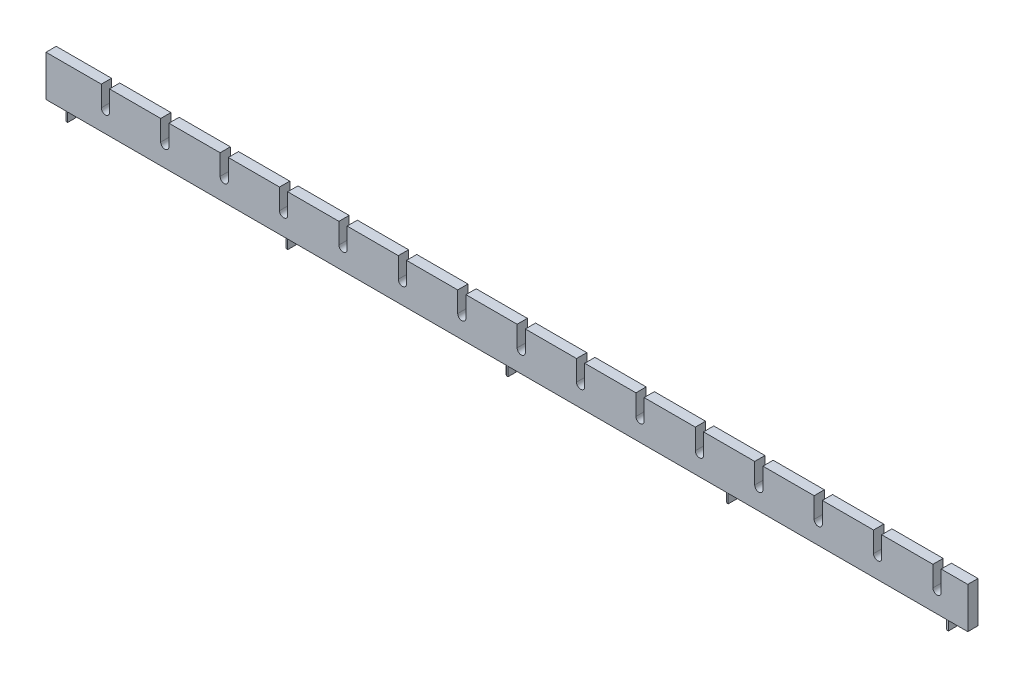
SolidWorks part; units mm, degrees
material "PPE"
ref_plane "Front Plane" through (0, 0, 0) normal (0, 0, 1) x (1, 0, 0)
ref_plane "Top Plane" through (0, 0, 0) normal (0, 1, 0) x (1, 0, 0)
ref_plane "Right Plane" through (0, 0, 0) normal (1, 0, 0) x (0, 0, -1)
sketch "Sketch1" plane through (0, 0, 0) normal (0, 1, 0) x (1, 0, 0)
  line L1 (-285.75, -3.175) -> (285.75, -3.175)
  line L2 (-285.75, -3.175) -> (-285.75, 3.175)
  line L3 (-285.75, 3.175) -> (285.75, 3.175)
  line L4 (285.75, -3.175) -> (285.75, 3.175)
  line L5 (-285.75, -3.175) -> (285.75, 3.175) construction
  line L6 (-285.75, 3.175) -> (285.75, -3.175) construction
  point P0 (0, 0)
  dimension "D1" = 6.35
  dimension "D2" = 571.5
extrude "Boss-Extrude1" add sketch "Sketch1" along normal blind 25.4 contours L2 L3 L4 L1
sketch "Sketch2" plane through (0, 0, 0) normal (0, -1, 0) x (1, 0, 0)
  line L0 (-273.05, 2.54) -> (-273.05, -2.54)
  line L1 (-136.525, 2.54) -> (-136.525, -2.54)
  line L2 (0, 2.54) -> (0, -2.54)
  line L3 (136.525, 2.54) -> (136.525, -2.54)
  line L4 (273.05, 2.54) -> (273.05, -2.54)
  line L5 (-285.75, 3.175) -> (-285.75, -3.175) construction
  arc A4 (-273.05, 2.54) -> (-273.05, -2.54) centre (-273.05, 0) ccw
  arc A5 (-136.525, 2.54) -> (-136.525, -2.54) centre (-136.525, 0) ccw
  arc A6 (0, 2.54) -> (0, -2.54) centre (0, 0) ccw
  arc A7 (136.525, 2.54) -> (136.525, -2.54) centre (136.525, 0) ccw
  arc A8 (273.05, 2.54) -> (273.05, -2.54) centre (273.05, 0) ccw
  dimension "D1" = 5
  dimension "D4" = 5.08
  dimension "D3" = 12.7
extrude "Boss-Extrude2" add sketch "Sketch2" along normal blind 6.35
sketch "Sketch3" plane through (0, 0, 3.175) normal (0, 0, 1) x (1, 0, 0)
  line L0 (-248.92, 38.1) -> (-248.92, 12.7) construction
  line L1 (-285.75, 25.4) -> (285.75, 25.4) construction
  line L2 (-246.38, 38.1) -> (-246.38, 12.7)
  line L3 (-251.46, 38.1) -> (-251.46, 12.7)
  line L4 (-212.09, 38.1) -> (-212.09, 12.7) construction
  line L5 (-209.55, 38.1) -> (-209.55, 12.7)
  line L6 (-214.63, 38.1) -> (-214.63, 12.7)
  line L7 (-175.26, 38.1) -> (-175.26, 12.7) construction
  line L8 (-172.72, 38.1) -> (-172.72, 12.7)
  line L9 (-177.8, 38.1) -> (-177.8, 12.7)
  line L10 (-138.43, 38.1) -> (-138.43, 12.7) construction
  line L13 (-135.89, 38.1) -> (-135.89, 12.7)
  line L16 (-140.97, 38.1) -> (-140.97, 12.7)
  line L19 (-101.6, 38.1) -> (-101.6, 12.7) construction
  line L22 (-99.06, 38.1) -> (-99.06, 12.7)
  line L25 (-104.14, 38.1) -> (-104.14, 12.7)
  line L28 (-285.75, 25.4) -> (-285.75, 0) construction
  line L29 (-64.77, 38.1) -> (-64.77, 12.7) construction
  line L30 (-62.23, 38.1) -> (-62.23, 12.7)
  line L31 (-67.31, 38.1) -> (-67.31, 12.7)
  line L32 (-27.94, 38.1) -> (-27.94, 12.7) construction
  line L33 (-25.4, 38.1) -> (-25.4, 12.7)
  line L34 (-30.48, 38.1) -> (-30.48, 12.7)
  line L35 (8.89, 38.1) -> (8.89, 12.7) construction
  line L36 (11.43, 38.1) -> (11.43, 12.7)
  line L37 (6.35, 38.1) -> (6.35, 12.7)
  line L38 (45.72, 38.1) -> (45.72, 12.7) construction
  line L39 (48.26, 38.1) -> (48.26, 12.7)
  line L40 (43.18, 38.1) -> (43.18, 12.7)
  line L41 (82.55, 38.1) -> (82.55, 12.7) construction
  line L42 (85.09, 38.1) -> (85.09, 12.7)
  line L43 (80.01, 38.1) -> (80.01, 12.7)
  line L44 (119.38, 38.1) -> (119.38, 12.7) construction
  line L45 (121.92, 38.1) -> (121.92, 12.7)
  line L46 (116.84, 38.1) -> (116.84, 12.7)
  line L47 (156.21, 38.1) -> (156.21, 12.7) construction
  line L48 (158.75, 38.1) -> (158.75, 12.7)
  line L49 (153.67, 38.1) -> (153.67, 12.7)
  line L50 (193.04, 38.1) -> (193.04, 12.7) construction
  line L51 (195.58, 38.1) -> (195.58, 12.7)
  line L52 (190.5, 38.1) -> (190.5, 12.7)
  line L53 (229.87, 38.1) -> (229.87, 12.7) construction
  line L54 (232.41, 38.1) -> (232.41, 12.7)
  line L55 (227.33, 38.1) -> (227.33, 12.7)
  line L56 (266.7, 38.1) -> (266.7, 12.7) construction
  line L57 (269.24, 38.1) -> (269.24, 12.7)
  line L58 (264.16, 38.1) -> (264.16, 12.7)
  arc A0 (-246.38, 38.1) -> (-251.46, 38.1) centre (-248.92, 38.1) ccw
  arc A1 (-251.46, 12.7) -> (-246.38, 12.7) centre (-248.92, 12.7) ccw
  arc A2 (-209.55, 38.1) -> (-214.63, 38.1) centre (-212.09, 38.1) ccw
  arc A3 (-214.63, 12.7) -> (-209.55, 12.7) centre (-212.09, 12.7) ccw
  arc A4 (-172.72, 38.1) -> (-177.8, 38.1) centre (-175.26, 38.1) ccw
  arc A5 (-177.8, 12.7) -> (-172.72, 12.7) centre (-175.26, 12.7) ccw
  arc A6 (-135.89, 38.1) -> (-140.97, 38.1) centre (-138.43, 38.1) ccw
  arc A7 (-140.97, 12.7) -> (-135.89, 12.7) centre (-138.43, 12.7) ccw
  arc A8 (-99.06, 38.1) -> (-104.14, 38.1) centre (-101.6, 38.1) ccw
  arc A9 (-104.14, 12.7) -> (-99.06, 12.7) centre (-101.6, 12.7) ccw
  arc A10 (-62.23, 38.1) -> (-67.31, 38.1) centre (-64.77, 38.1) ccw
  arc A11 (-67.31, 12.7) -> (-62.23, 12.7) centre (-64.77, 12.7) ccw
  arc A12 (-25.4, 38.1) -> (-30.48, 38.1) centre (-27.94, 38.1) ccw
  arc A13 (-30.48, 12.7) -> (-25.4, 12.7) centre (-27.94, 12.7) ccw
  arc A14 (11.43, 38.1) -> (6.35, 38.1) centre (8.89, 38.1) ccw
  arc A15 (6.35, 12.7) -> (11.43, 12.7) centre (8.89, 12.7) ccw
  arc A16 (48.26, 38.1) -> (43.18, 38.1) centre (45.72, 38.1) ccw
  arc A17 (43.18, 12.7) -> (48.26, 12.7) centre (45.72, 12.7) ccw
  arc A18 (85.09, 38.1) -> (80.01, 38.1) centre (82.55, 38.1) ccw
  arc A19 (80.01, 12.7) -> (85.09, 12.7) centre (82.55, 12.7) ccw
  arc A20 (121.92, 38.1) -> (116.84, 38.1) centre (119.38, 38.1) ccw
  arc A21 (116.84, 12.7) -> (121.92, 12.7) centre (119.38, 12.7) ccw
  arc A22 (158.75, 38.1) -> (153.67, 38.1) centre (156.21, 38.1) ccw
  arc A23 (153.67, 12.7) -> (158.75, 12.7) centre (156.21, 12.7) ccw
  arc A24 (195.58, 38.1) -> (190.5, 38.1) centre (193.04, 38.1) ccw
  arc A25 (190.5, 12.7) -> (195.58, 12.7) centre (193.04, 12.7) ccw
  arc A26 (232.41, 38.1) -> (227.33, 38.1) centre (229.87, 38.1) ccw
  arc A27 (227.33, 12.7) -> (232.41, 12.7) centre (229.87, 12.7) ccw
  arc A28 (269.24, 38.1) -> (264.16, 38.1) centre (266.7, 38.1) ccw
  arc A29 (264.16, 12.7) -> (269.24, 12.7) centre (266.7, 12.7) ccw
  point P4 (-248.92, 25.4)
  point P14 (-212.09, 25.4)
  point P21 (-175.26, 25.4)
  point P28 (-138.43, 25.4)
  point P35 (-101.6, 25.4)
  point P42 (-64.77, 25.4)
  point P49 (-27.94, 25.4)
  point P56 (8.89, 25.4)
  point P63 (45.72, 25.4)
  point P70 (82.55, 25.4)
  point P77 (119.38, 25.4)
  point P84 (156.21, 25.4)
  point P91 (193.04, 25.4)
  point P98 (229.87, 25.4)
  point P105 (266.7, 25.4)
  dimension "D1" = 5.08
  dimension "D2" = 12.7
  dimension "D3" = 36.83
  dimension "D5" = 31.75
  dimension "D4" = 15
extrude "Cut-Extrude1" cut sketch "Sketch3" against normal through all
